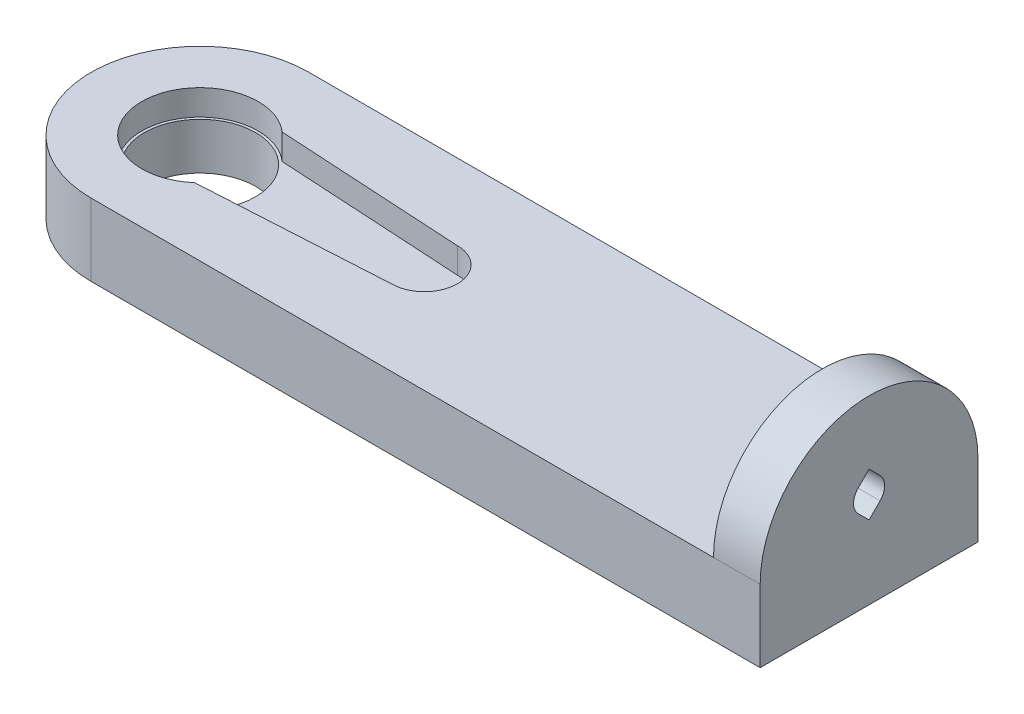
SolidWorks part; units mm, degrees
ref_plane "Front Plane" through (0, 0, 0) normal (0, 0, 1) x (1, 0, 0)
ref_plane "Top Plane" through (0, 0, 0) normal (0, 1, 0) x (1, 0, 0)
ref_plane "Right Plane" through (0, 0, 0) normal (1, 0, 0) x (0, 0, -1)
sketch "Sketch1" plane through (0, 0, 0) normal (0, 1, 0) x (1, 0, 0)
  line L0 (0, 0) -> (40, 0) construction
  line L1 (0, 7) -> (40, 7)
  line L2 (0, -7) -> (40, -7)
  line L3 (40, -7) -> (40, 7)
  arc A0 (0, 7) -> (0, -7) centre (0, 0) ccw
  point P3 (0, 7)
  point P8 (11.157, -25.423)
  dimension "D1" = 7
  dimension "D2" = 40
extrude "Boss-Extrude1" add sketch "Sketch1" along normal blind 3
sketch "Sketch2" plane through (0, 0, 0) normal (0, -1, 0) x (1, 0, 0)
  circle A0 centre (0, 0) radius 3.575
  dimension "D1" = 7.15
extrude "Cut-Extrude1" cut sketch "Sketch2" against normal blind 3.95
sketch "Sketch3" plane through (0, 3, 0) normal (0, 1, 0) x (1, 0, 0)
  line L0 (2.3996, 2.65) -> (2.3996, -2.65) construction
  line L1 (3.575, 0) -> (16.375, 0) construction
  line L2 (2.3996, -2.65) -> (14.425, -1.95) construction
  line L3 (14.425, -1.95) -> (14.425, 1.95) construction
  line L4 (14.425, 1.95) -> (2.3996, 2.65) construction
  line L5 (14.43, 2.12) -> (2.4685, 2.8163)
  line L6 (2.4685, -2.8163) -> (14.43, -2.12)
  line L7 (40, -7) -> (40, 7)
  line L11 (0, -7) -> (40, -7)
  line L12 (40, 7) -> (0, 7)
  line L13 (0, -7) -> (40, -7)
  line L14 (40, 7) -> (0, 7)
  line L15 (40, -7) -> (40, 7)
  arc A1 (14.425, -1.95) -> (14.425, 1.95) centre (14.425, 0) ccw construction
  circle A2 centre (0, 0) radius 3.575 construction
  circle A3 centre (14.425, 0) radius 1.95 construction
  circle A4 centre (0, 0) radius 3.575 construction
  arc A5 (2.3996, -2.65) -> (2.3996, 2.65) centre (0, 0) cw construction
  arc A7 (2.4685, -2.8163) -> (2.4685, 2.8163) centre (0, 0) cw
  arc A8 (14.43, -2.12) -> (14.43, 2.12) centre (14.425, 0) ccw
  arc A12 (0, 7) -> (0, -7) centre (0, 0) ccw
  arc A14 (0, 7) -> (0, -7) centre (0, 0) ccw
  point P3 (0, 0)
  point P4 (2.3996, 0)
  point P26 (40.4172, 7)
  dimension "D5" = 0
  dimension "D3" = 3.9
  dimension "D1" = 5.3
  dimension "D2" = 12.8
  dimension "D4" = 0.17
extrude "Boss-Extrude2" add sketch "Sketch3" along normal blind 1.64
sketch "Sketch9" plane through (40, 0, 0) normal (1, 0, 0) x (0, 0, -1)
  line L0 (-7, 4.64) -> (7, 4.64) construction
  line L1 (-7, 4.64) -> (-7, 0)
  line L2 (-7, 0) -> (7, 0)
  line L3 (7, 0) -> (7, 4.64)
  arc A0 (-7, 4.64) -> (7, 4.64) centre (0, 4.64) cw
extrude "Boss-Extrude6" add sketch "Sketch9" along normal blind 3
sketch "Sketch11" plane through (43, 0, 0) normal (1, 0, 0) x (0, 0, -1)
  line L0 (0, 4.7258) -> (0, 7.5542) construction
  line L1 (0, 7.5542) -> (-1.4142, 6.14) construction
  line L2 (-1.4142, 6.14) -> (0, 4.7258) construction
  line L3 (0, 4.7258) -> (1.4142, 6.14) construction
  line L4 (1.4142, 6.14) -> (0, 7.5542) construction
  line L5 (-1.4142, 6.14) -> (0, 7.5542)
  line L6 (0, 7.5542) -> (1.4142, 6.14)
  line L7 (1.4142, 6.14) -> (0, 4.7258)
  line L8 (0, 4.7258) -> (-1.4142, 6.14)
  line L9 (7, 0) -> (7, 4.64) construction
  circle A0 centre (0, 6.14) radius 1
  point P3 (0, 6.5329)
  point P6 (0, 6.14)
  point P12 (0.1391, 6.14)
  point P13 (0, 0)
  dimension "D1" = 2
  dimension "D2" = 1.5
  dimension "D3" = 7
extrude "Cut-Extrude8" cut sketch "Sketch11" against normal up to next contours A0 L6 L5 | A0 L8 L7 | A0
